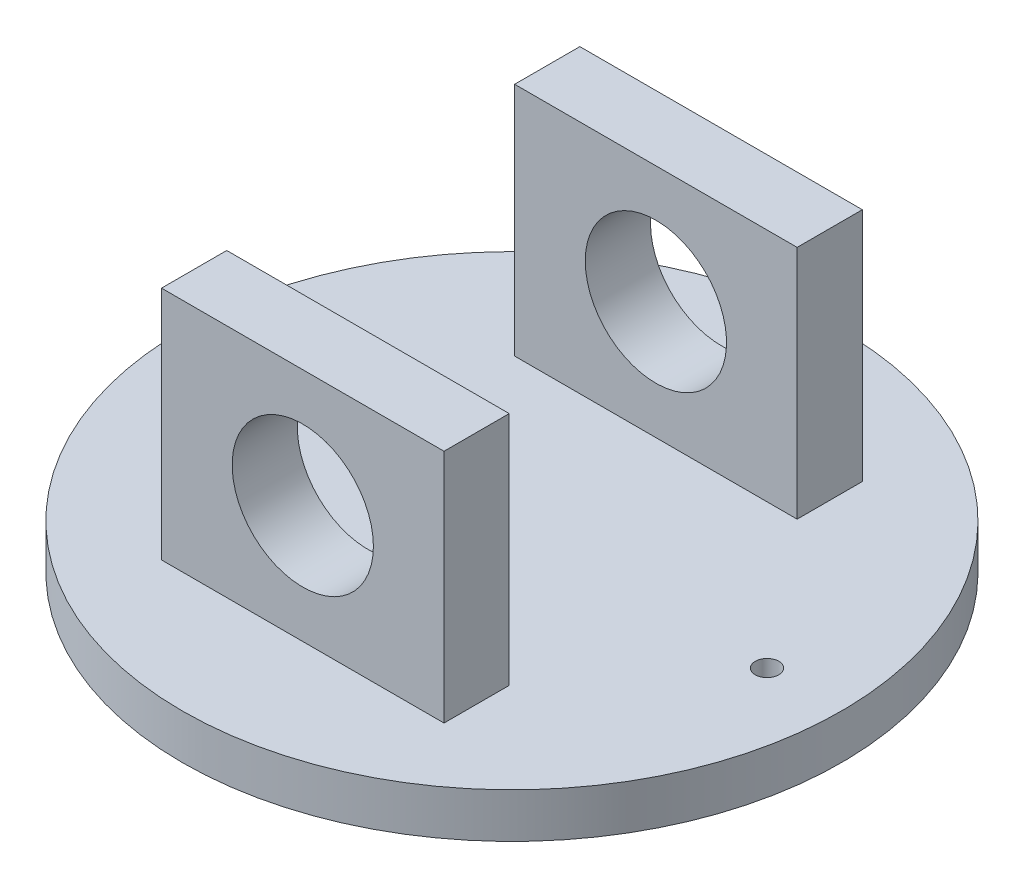
SolidWorks part; units mm, degrees
ref_plane "前视基准面" through (0, 0, 0) normal (0, 0, 1) x (1, 0, 0)
ref_plane "上视基准面" through (0, 0, 0) normal (0, 1, 0) x (1, 0, 0)
ref_plane "右视基准面" through (0, 0, 0) normal (1, 0, 0) x (0, 0, -1)
other "Configuration Table"
sketch "草图4" plane through (0, 0, 0) normal (0, 1, 0) x (1, 0, 0)
  circle A0 centre (0, 0) radius 2.5
  dimension "D1" = 5
extrude "凸台-拉伸3" add sketch "草图4" along normal blind 25
sketch "草图5" plane through (0, 25, 0) normal (0, 1, 0) x (1, 0, 0)
  circle A0 centre (0, 0) radius 7.5
  dimension "D1" = 15
extrude "凸台-拉伸4" add sketch "草图5" along normal blind 25
sketch "草图6" plane through (0, 50, 0) normal (0, 1, 0) x (1, 0, 0)
  circle A0 centre (0, 0) radius 139.9997
extrude "凸台-拉伸5" add sketch "草图6" against normal blind 19
sketch "草图15" plane through (0, 50, 0) normal (0, 1, 0) x (1, 0, 0)
  line L0 (0, 0) -> (-216.9712, 0) construction
  line L1 (-60, 88.85) -> (60, 88.85)
  line L2 (-60, 88.85) -> (-60, 61.15)
  line L3 (-60, 61.15) -> (60, 61.15)
  line L4 (60, 88.85) -> (60, 61.15)
  line L5 (-60, 88.85) -> (60, 61.15) construction
  line L6 (-60, 61.15) -> (60, 88.85) construction
  line L7 (-60, -61.15) -> (60, -61.15)
  line L8 (60, -88.85) -> (60, -61.15)
  line L9 (-60, -88.85) -> (60, -88.85)
  line L10 (-60, -88.85) -> (-60, -61.15)
  point P0 (0, 75)
  dimension "D2" = 120
  dimension "D3" = 27.7
extrude "凸台-拉伸7" add sketch "草图15" along normal blind 100
sketch "草图16" plane through (0, 0, 88.85) normal (0, 0, 1) x (1, 0, 0)
  circle A0 centre (0, 100) radius 30
  dimension "D1" = 60
extrude "切除-拉伸3" cut sketch "草图16" against normal up to next contours A0
sketch "草图17" plane through (0, 0, -88.85) normal (0, 0, -1) x (-1, 0, 0)
  circle A0 centre (0, 100) radius 30
  dimension "D1" = 60
extrude "切除-拉伸4" cut sketch "草图17" against normal up to next contours A0
sketch "草图18" plane through (0, 31, 0) normal (0, -1, 0) x (1, 0, 0)
  circle A0 centre (0, 0) radius 17.25 construction
  circle A1 centre (0, 17.25) radius 2
  circle A2 centre (14.9389, 8.625) radius 2
  circle A3 centre (14.9389, -8.625) radius 2
  circle A4 centre (0, -17.25) radius 2
  circle A5 centre (-14.9389, -8.625) radius 2
  circle A6 centre (-14.9389, 8.625) radius 2
  point P18 (0, 0)
  dimension "D1" = 34.5
  dimension "D2" = 4
  dimension "D3" = 6
extrude "凸台-拉伸8" add sketch "草图18" along normal blind 30
sketch "草图19" plane through (0, 50, 0) normal (0, 1, 0) x (1, 0, 0)
  circle A0 centre (108.3782, 0) radius 5
  dimension "D1" = 10
extrude "切除-拉伸5" cut sketch "草图19" against normal through all both and the other way through all
mirror "镜向1" about plane through (0, 0, 0) normal (1, 0, 0) of "切除-拉伸5"
